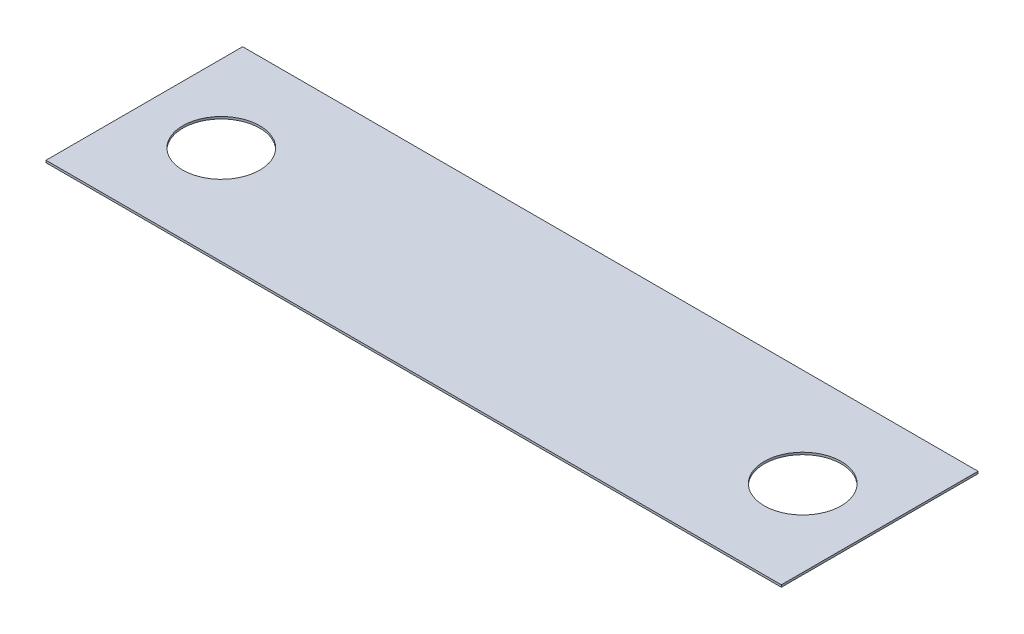
SolidWorks part; units mm, degrees
material "Low Carbon Cold Rolled"
ref_plane "Front Plane" through (0, 0, 0) normal (0, 0, 1) x (1, 0, 0)
ref_plane "Top Plane" through (0, 0, 0) normal (0, 1, 0) x (1, 0, 0)
ref_plane "Right Plane" through (0, 0, 0) normal (1, 0, 0) x (0, 0, -1)
sketch "Sketch1" plane through (0, 0, 0) normal (0, 1, 0) x (1, 0, 0)
  line L1 (0, 0) -> (86, 0)
  line L2 (0, 0) -> (0, 23)
  line L3 (0, 23) -> (86, 23)
  line L4 (86, 0) -> (86, 23)
  dimension "D1" = 86
  dimension "D2" = 23
extrude "Extrude1" add sketch "Sketch1" along normal blind 0.254
hole_wizard "Ø9.0 (9) Diameter Hole1" positions "Sketch3" profile "Sketch4" hole size "Ø9.0" standard "Ansi Metric" end condition through all
sketch "Sketch3" plane through (0, 0.254, 0) normal (0, 1, 0) x (-1, 0, 0)
  line L0 (-9, -11.5) -> (0, -11.5) construction
  line L1 (0, -23) -> (0, 0) construction
  line L3 (-77, -11.5) -> (-9, -11.5) construction
  line L5 (-43, -11.5) -> (-43, -23) construction
  line L6 (-86, -23) -> (0, -23) construction
  point P0 (-9, -11.5)
  point P1 (-77, -11.5)
  dimension "D1" = 68
sketch "Sketch4" plane through (9, 0.254, -11.5) normal (1, 0, 0) x (0, 0, 1)
  line L0 (0, 0) -> (0, 0.254)
  line L1 (0, 0.254) -> (4.5, 0.254)
  line L2 (4.5, 0.254) -> (4.5, 0)
  line L5 (4.5, 0) -> (0, 0)
  line L11 (0, -6.35) -> (0, 107.95) construction
  dimension "Thru Hole Dia." = 9
  dimension "Thru Hole Depth" = 0.254
